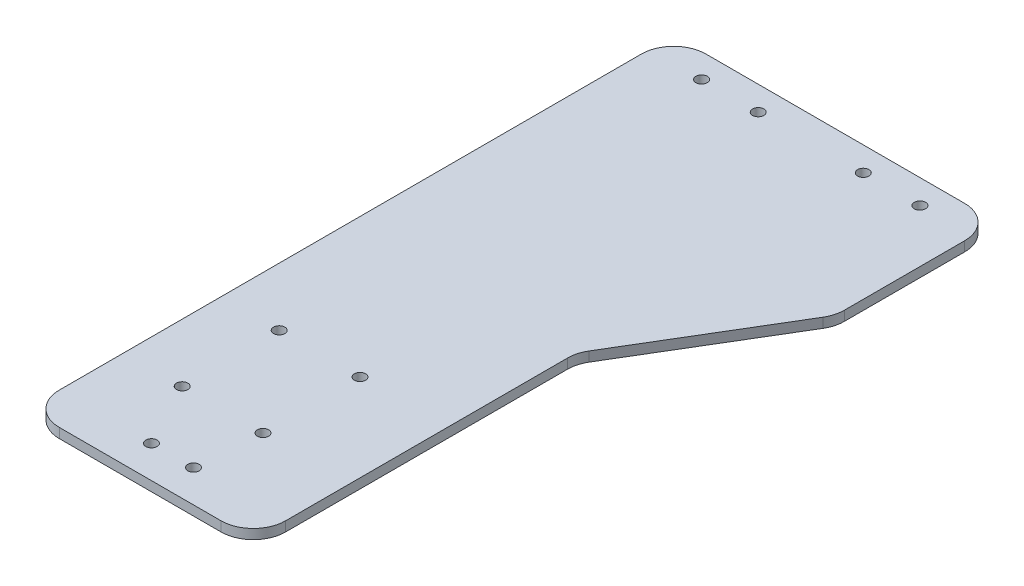
SolidWorks part; units mm, degrees
ref_plane "前视基准面" through (0, 0, 0) normal (0, 0, 1) x (1, 0, 0)
ref_plane "上视基准面" through (0, 0, 0) normal (0, 1, 0) x (1, 0, 0)
ref_plane "右视基准面" through (0, 0, 0) normal (1, 0, 0) x (0, 0, -1)
other "Configuration Table"
sketch "草图1" plane through (0, 0, 0) normal (0, 1, 0) x (1, 0, 0)
  line L1 (-50, -100) -> (50, -100)
  line L2 (-50, -100) -> (-50, 100)
  line L3 (-50, 100) -> (50, 100)
  line L4 (50, -100) -> (50, 100)
  line L5 (-50, -100) -> (50, 100) construction
  line L6 (-50, 100) -> (50, -100) construction
  point P0 (0, 0)
  dimension "D1" = 100
  dimension "D2" = 200
extrude "凸台-拉伸1" add sketch "草图1" along normal blind 3
sketch "草图3" plane through (0, 3, 0) normal (0, 1, 0) x (1, 0, 0)
  line L0 (20, -100) -> (20, 0)
  line L1 (-50, -100) -> (50, -100) construction
  line L2 (20, 0) -> (50, 50)
  line L3 (50, -100) -> (50, 100) construction
  line L4 (50, 50) -> (50, -100)
  line L5 (50, -100) -> (20, -100)
  dimension "D1" = 30
  dimension "D2" = 150
  dimension "D3" = 100
extrude "切除-拉伸1" cut sketch "草图3" against normal blind 10
fillet "圆角2" radius 10 6 edges at (50, 1.5, -100) (-50, 1.5, -100) (-50, 1.5, 100) (20, 1.5, 100) (20, 1.5, 0) (50, 1.5, -50)
sketch "草图4" plane through (0, 3, 0) normal (0, 1, 0) x (1, 0, 0)
  circle A0 centre (33.6474, 92.5) radius 1.75
  circle A1 centre (16.1327, 92.5) radius 1.75
  circle A2 centre (-33.8673, 92.5) radius 1.75
  circle A3 centre (-16.3526, 92.5) radius 1.75
extrude "切除-拉伸2" cut sketch "草图4" against normal blind 21
sketch "草图5" plane through (0, 0, 0) normal (0, -1, 0) x (1, 0, 0)
  circle A0 centre (-8.5, 90) radius 1.75
  circle A1 centre (-21.5, 90) radius 1.75
extrude "切除-拉伸3" cut sketch "草图5" against normal blind 4
sketch "草图7" plane through (0, 3, 0) normal (0, 1, 0) x (1, 0, 0)
  line L0 (-36.75, -40) -> (49963.25, -40) construction
  line L1 (-50, 90) -> (-50, -90) construction
  line L2 (-45, -55) -> (49955, -55) construction
  line L3 (-45, -75) -> (-45, -35) construction
  line L4 (6, -35) -> (6, -75) construction
  arc A0 (-35, -38.25) -> (-35, -41.75) centre (-35, -40) ccw construction
  arc A1 (-5, -41.75) -> (-5, -38.25) centre (-5, -40) ccw construction
  circle A2 centre (-32, -40) radius 1.75
  circle A3 centre (-7, -40) radius 1.75
  circle A4 centre (-7, -70) radius 1.75
  circle A5 centre (-32, -70) radius 1.75
  point P5 (-36.75, -40)
  point P9 (-3.25, -40)
  point P20 (-45, -55)
  point P23 (6, -55)
  dimension "D1" = 25
  dimension "D2" = 3.5
  dimension "D3" = 18
extrude "切除-拉伸4" cut sketch "草图7" against normal blind 4
